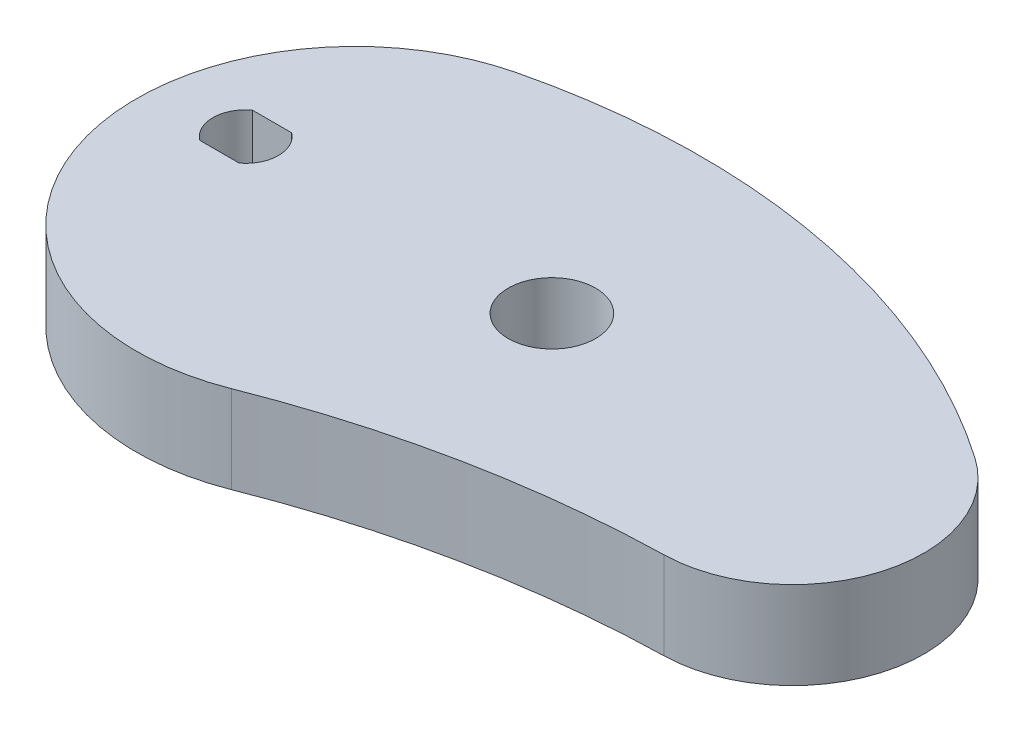
SolidWorks part; units mm, degrees
ref_plane "Front Plane" through (0, 0, 0) normal (0, 0, 1) x (1, 0, 0)
ref_plane "Top Plane" through (0, 0, 0) normal (0, 1, 0) x (1, 0, 0)
ref_plane "Right Plane" through (0, 0, 0) normal (1, 0, 0) x (0, 0, -1)
sketch "Sketch1" plane through (0, 0, 0) normal (0, 1, 0) x (1, 0, 0)
  line L0 (-38.1, 6.35) -> (50.8, 6.35) construction
  line L1 (-43.815, 13.97) -> (-32.385, 13.97)
  line L2 (-43.815, -1.27) -> (-32.385, -1.27)
  arc A0 (-15.0091, 61.7007) -> (23.2103, -59.1061) centre (0, 0) ccw
  arc A1 (127.8467, -38.0906) -> (148.6877, 31.325) centre (127, 0) ccw
  arc A2 (-15.0091, 61.7007) -> (148.6877, 31.325) centre (33.02, -135.7416) cw
  arc A3 (127.8467, -38.0906) -> (23.2103, -59.1061) centre (134.62, -342.8153) ccw
  circle A4 centre (50.8, 6.35) radius 12.7
  arc A5 (-43.815, 13.97) -> (-43.815, -1.27) centre (-38.1, 6.35) ccw
  arc A6 (-32.385, -1.27) -> (-32.385, 13.97) centre (-38.1, 6.35) ccw
  dimension "D1" = 25.4
  dimension "D2" = 50.8
  dimension "D3" = 63.5
  dimension "D4" = 38.1
  dimension "D5" = 203.2
  dimension "D6" = 304.8
  dimension "D7" = 76.2
  dimension "D9" = 19.05
  dimension "D8" = 6.35
  dimension "D10" = 88.9
  dimension "D11" = 7.62
extrude "Extrude1" add sketch "Sketch1" along normal blind 25.4
